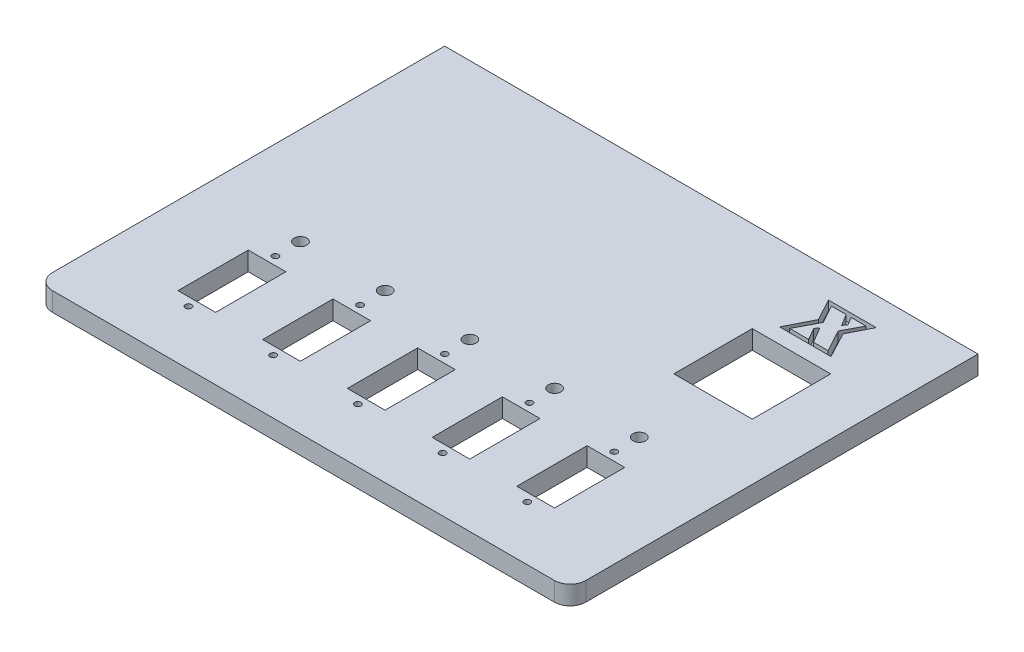
SolidWorks part; units mm, degrees
ref_plane "Front Plane" through (0, 0, 0) normal (0, 0, 1) x (1, 0, 0)
ref_plane "Top Plane" through (0, 0, 0) normal (0, 1, 0) x (1, 0, 0)
ref_plane "Right Plane" through (0, 0, 0) normal (1, 0, 0) x (0, 0, -1)
sketch "Sketch1" plane through (0, 0, 0) normal (0, 1, 0) x (1, 0, 0)
  line L1 (-85, -65) -> (85, -65)
  line L2 (-85, -65) -> (-85, 65)
  line L3 (-85, 65) -> (85, 65)
  line L4 (85, -65) -> (85, 65)
  line L5 (-85, -65) -> (85, 65) construction
  line L6 (-85, 65) -> (85, -65) construction
  point P0 (0, 0)
  dimension "D1" = 170
  dimension "D2" = 130
extrude "Boss-Extrude1" add sketch "Sketch1" along normal blind 6
sketch "Sketch2" plane through (0, 6, 0) normal (0, 1, 0) x (1, 0, 0)
  line L0 (-85, 65) -> (-85, -65) construction
  line L1 (-60, -45) -> (-48, -45)
  line L2 (-60, -45) -> (-60, -22.6)
  line L3 (-60, -22.6) -> (-48, -22.6)
  line L4 (-48, -45) -> (-48, -22.6)
  line L5 (-60, -45) -> (-48, -22.6) construction
  line L6 (-60, -22.6) -> (-48, -45) construction
  line L7 (-85, -65) -> (85, -65) construction
  circle A0 centre (-54, -19.95) radius 1
  circle A1 centre (-54, -47.65) radius 1
  circle A2 centre (-54, -11.95) radius 2
  point P0 (-54, -51.3962)
  point P14 (-54, -33.8)
  dimension "D5" = 2
  dimension "D6" = 2
  dimension "D12" = 4
  dimension "D13" = 8
  dimension "D14" = 6
  dimension "D15" = 6
  dimension "D1" = 12
  dimension "D2" = 22.4
  dimension "D3" = 25
  dimension "D4" = 20
  dimension "D7" = 27.7
  dimension "D8" = 2.65
  dimension "D9" = 2.65
  dimension "D10" = 13.85
  dimension "D11" = 13.85
extrude "Cut-Extrude1" cut sketch "Sketch2" against normal blind 10
pattern_linear "LPattern1" count 5 spacing 27 along (1, 0, 0) of "Cut-Extrude1"
sketch "Sketch8" plane through (0, 6, 0) normal (0, 1, 0) x (1, 0, 0)
  line L0 (85, 65) -> (-85, 65) construction
  line L1 (67, 11.05) -> (42, 11.05)
  line L2 (67, 11.05) -> (67, 36.05)
  line L3 (67, 36.05) -> (42, 36.05)
  line L4 (42, 11.05) -> (42, 36.05)
  line L6 (85, -65) -> (85, 65) construction
  dimension "D1" = 25
  dimension "D2" = 25
  dimension "D4" = 18
  dimension "D5" = 28.95
extrude "Cut-Extrude5" cut sketch "Sketch8" against normal through all
fillet "Fillet2" radius 5 2 edges at (-85, 3, 65) (85, 3, 65)
sketch "Sketch10" plane through (0, 0, 0) normal (0, -1, 0) x (1, 0, 0)
  line L0 (-80, 65) -> (80, 65) construction
  line L1 (-85, -65) -> (-85, 60) construction
  circle A0 centre (-73, 53) radius 9
  dimension "D1" = 18
  dimension "D3" = 12
  dimension "D2" = 12
extrude "Cut-Extrude6" cut sketch "Sketch10" against normal blind 2.6
mirror "Mirror1" about plane through (0, 0, 0) normal (1, 0, 0) of "Cut-Extrude6"
mirror "Mirror2" about plane through (0, 0, 0) normal (0, 0, 1) of "Mirror1", "Cut-Extrude6"
sketch "Sketch11" plane through (0, 6, 0) normal (0, 1, 0) x (1, 0, 0)
  text T0 "<b>X</b>" font "G2 Geometr885 BT" height 15
  dimension "D1" = 3.7
extrude "Cut-Extrude7" cut sketch "Sketch11" against normal blind 3
